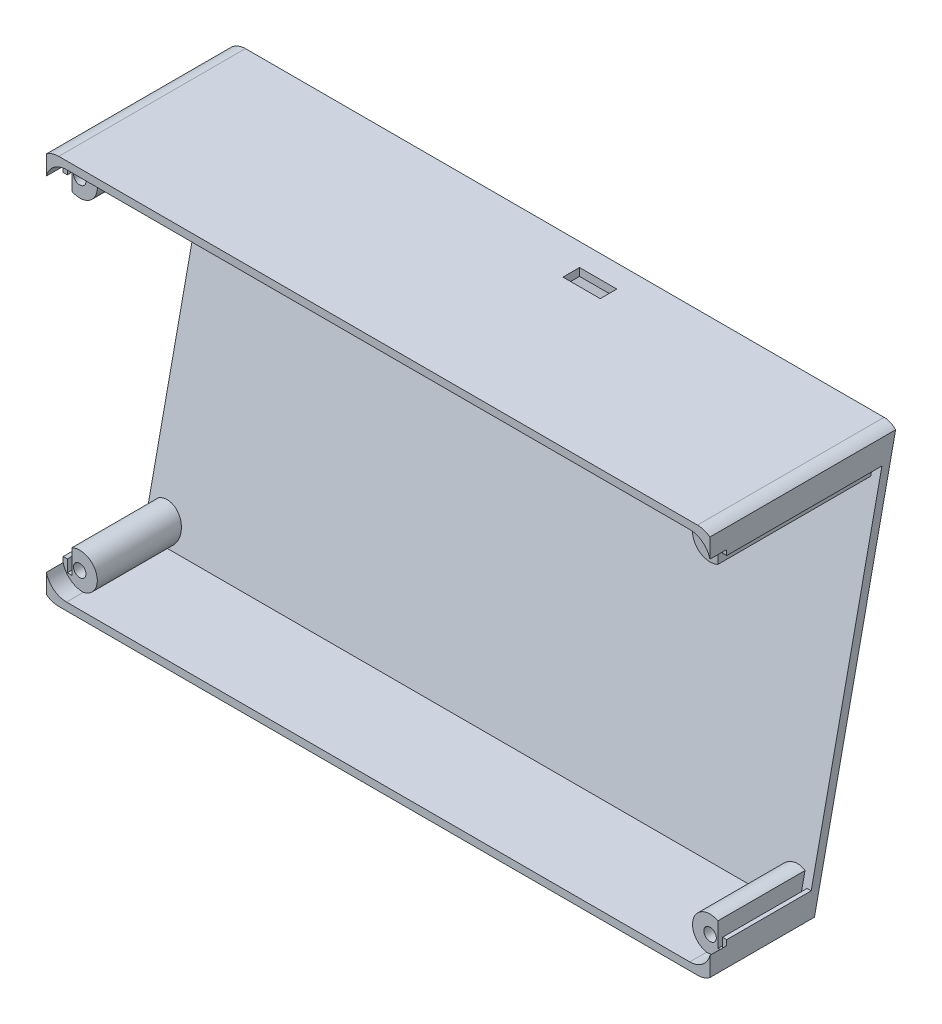
SolidWorks part; units mm, degrees
material "Nylon 101"
ref_plane "Ebene vorne" through (0, 0, 0) normal (0, 0, 1) x (1, 0, 0)
ref_plane "Ebene oben" through (0, 0, 0) normal (0, 1, 0) x (1, 0, 0)
ref_plane "Ebene rechts" through (0, 0, 0) normal (1, 0, 0) x (0, 0, -1)
sketch "Skizze1" plane through (0, 0, 0) normal (0, 0, 1) x (1, 0, 0)
  line L1 (-82, -47) -> (82, -47)
  line L2 (-82, -47) -> (-82, 47)
  line L3 (-82, 47) -> (82, 47)
  line L4 (82, -47) -> (82, 47)
  line L5 (-82, -47) -> (82, 47) construction
  line L6 (-82, 47) -> (82, -47) construction
  point P0 (0, 0)
  dimension "D1" = 164
  dimension "D2" = 94
extrude "Aufsatz-Linear austragen1" add sketch "Skizze1" along normal blind 25
sketch "Skizze2" plane through (82, 0, 0) normal (1, 0, 0) x (0, 0, -1)
  line L0 (0, -47) -> (0, 47)
  line L1 (0, 47) -> (20, 47)
  line L2 (20, 47) -> (0, -47)
  dimension "D1" = 20
extrude "Aufsatz-Linear austragen2" add sketch "Skizze2" against normal up to vertex (164 mm away) up to point (-82, 47, 0)
sketch "Skizze3" plane through (0, 0, 25) normal (0, 0, 1) x (1, 0, 0)
  line L1 (-75.15, -45.15) -> (75.15, -45.15)
  line L2 (-80.15, -40.15) -> (-80.15, 40.15)
  line L3 (-75.15, 45.15) -> (75.15, 45.15)
  line L4 (80.15, -40.15) -> (80.15, 40.15)
  line L5 (-80.15, -45.15) -> (80.15, 45.15) construction
  line L6 (-80.15, 45.15) -> (80.15, -45.15) construction
  arc A0 (80.15, 40.15) -> (75.15, 45.15) centre (75.15, 40.15) ccw
  arc A1 (80.15, -40.15) -> (75.15, -45.15) centre (75.15, -40.15) cw
  arc A2 (-80.15, -40.15) -> (-75.15, -45.15) centre (-75.15, -40.15) ccw
  arc A3 (-80.15, 40.15) -> (-75.15, 45.15) centre (-75.15, 40.15) cw
  point P1 (0, 0)
  dimension "D3" = 5
  dimension "D1" = 160.3
  dimension "D2" = 90.3
extrude "Schnitt-Linear austragen1" cut sketch "Skizze3" against normal offset from surface (24.4127 mm away) 2
sketch "Skizze4" plane through (0, 0, 25) normal (0, 0, 1) x (1, 0, 0)
  line L0 (75.15, 45.15) -> (-75.15, 45.15) construction
  line L1 (-80.15, 40.15) -> (-80.15, -40.15) construction
  line L2 (-75.15, -45.15) -> (75.15, -45.15) construction
  line L3 (80.15, -40.15) -> (80.15, 40.15) construction
  circle A0 centre (-76, 41) radius 1.5
  circle A1 centre (-76, 41) radius 4.2362
  circle A2 centre (-76, -41) radius 1.5
  circle A3 centre (-76, -41) radius 4.2362
  circle A4 centre (76, -41) radius 1.5
  circle A5 centre (76, -41) radius 4.2362
  circle A6 centre (76, 41) radius 1.5
  circle A7 centre (76, 41) radius 4.2362
  dimension "D3" = 3
  dimension "D4" = 3
  dimension "D7" = 3
  dimension "D10" = 3
  dimension "D1" = 4.15
  dimension "D2" = 4.15
  dimension "D5" = 4.15
  dimension "D6" = 4.15
  dimension "D8" = 4.15
  dimension "D9" = 4.15
  dimension "D11" = 4.15
  dimension "D12" = 4.15
extrude "Aufsatz-Linear austragen3" add sketch "Skizze4" against normal up to surface (41.6786 mm away)
sketch "Skizze6" plane through (0, 0, 25) normal (0, 0, 1) x (1, 0, 0)
  line L0 (-75.15, -45.15) -> (75.15, -45.15)
  line L1 (-80.15, -40.15) -> (-80.15, 40.15)
  line L2 (-75.15, 45.15) -> (75.15, 45.15)
  line L3 (80.15, -40.15) -> (80.15, 40.15)
  line L4 (-80.15, -45.15) -> (80.15, 45.15) construction
  line L5 (-80.15, 45.15) -> (80.15, -45.15) construction
  arc A0 (80.15, 40.15) -> (75.15, 45.15) centre (75.15, 40.15) ccw
  arc A1 (80.15, -40.15) -> (75.15, -45.15) centre (75.15, -40.15) cw
  arc A2 (-80.15, -40.15) -> (-75.15, -45.15) centre (-75.15, -40.15) ccw
  arc A3 (-80.15, 40.15) -> (-75.15, 45.15) centre (-75.15, 40.15) cw
  point P0 (0, 0)
  dimension "D3" = 5
  dimension "D1" = 160.3
  dimension "D2" = 90.3
  dimension "D4" = 0
  dimension "D5" = 0
extrude "Schnitt-Linear austragen2" cut sketch "Skizze6" against normal blind 4.05
fillet "Verrundung1" radius 5 4 edges at (82, 47, 2.5) (-82, 47, 2.5) (-82, -47, 12.5) (82, -47, 12.5)
sketch "Skizze7" plane through (0, 47, 0) normal (0, 1, 0) x (1, 0, 0)
  line L0 (75.15, 17.5616) -> (-75.15, 17.5616) construction
  line L1 (9, 14.5616) -> (18, 14.5616)
  line L2 (9, 14.5616) -> (9, 10.5616)
  line L3 (9, 10.5616) -> (18, 10.5616)
  line L4 (18, 14.5616) -> (18, 10.5616)
  line L5 (9, 14.5616) -> (18, 10.5616) construction
  line L6 (9, 10.5616) -> (18, 14.5616) construction
  point P0 (13.5, 12.5616)
  dimension "D1" = 13.5
  dimension "D2" = 3
  dimension "D3" = 9
  dimension "D4" = 4
extrude "Schnitt-Linear austragen4" cut sketch "Skizze7" against normal blind 4.05
sketch "Skizze8" plane through (0, -2.0355, -9.5669) normal (0, -0.2081, -0.9781) x (-1, 0, 0)
  line L0 (-82, -40.8591) -> (-82, 45.0212) construction
  line L1 (77, 50.1331) -> (-77, 50.1331) construction
  line L2 (82, -40.8591) -> (82, 45.0212) construction
  line L3 (77, -45.971) -> (-77, -45.971) construction
  circle A0 centre (-72, 40.1331) radius 5.5
  circle A1 centre (72, 40.1331) radius 5.5
  circle A2 centre (72, -35.971) radius 5.5
  circle A3 centre (-72, -35.971) radius 5.5
  dimension "D1" = 11
  dimension "D4" = 11
  dimension "D7" = 11
  dimension "D10" = 11
  dimension "D2" = 10
  dimension "D3" = 10
  dimension "D5" = 10
  dimension "D6" = 10
  dimension "D8" = 10
  dimension "D9" = 10
  dimension "D11" = 10
  dimension "D12" = 10
extrude "Schnitt-Linear austragen5" cut sketch "Skizze8" against normal blind 1
sketch "Skizze9" plane through (0, 0, 25) normal (0, 0, 1) x (1, 0, 0)
  line L2 (80, -71.5939) -> (80, 71.5939)
  line L4 (-80, -71.5939) -> (-80, 71.5939)
  line L7 (-80, 71.5939) -> (-121.6606, 71.5939)
  line L9 (-80, -71.5939) -> (-121.6606, -71.5939)
  line L10 (-121.6606, 71.5939) -> (-121.6606, -71.5939)
  line L11 (80, 71.5939) -> (127.6666, 71.5939)
  line L13 (80, -71.5939) -> (127.6666, -71.5939)
  line L14 (127.6666, 71.5939) -> (127.6666, -71.5939)
  point P0 (0, 0)
  dimension "D1" = 160
extrude "Schnitt-Linear austragen6" cut sketch "Skizze9" against normal through all
sketch "Skizze11" plane through (0, 0, 20.95) normal (0, 0, 1) x (1, 0, 0)
  line L0 (-80, 39.6054) -> (-80, -39.6054) construction
  line L1 (-77.9, 43) -> (-79, 43)
  line L2 (-77.9, 43) -> (-77.9, -43)
  line L3 (-77.9, -43) -> (-79, -43)
  line L4 (-79, 43) -> (-79, 40.1)
  line L6 (-79, 40.1) -> (-80, 40.1)
  line L8 (-79, -40.1) -> (-80, -40.1)
  line L9 (-80, 40.1) -> (-80, -40.1)
  line L17 (0, -24.75) -> (0, 24.75) construction
  line L18 (80, 40.1) -> (80, -40.1)
  line L19 (79, -40.1) -> (80, -40.1)
  line L21 (79, 40.1) -> (80, 40.1)
  line L22 (79, 43) -> (79, 40.1)
  line L23 (77.9, -43) -> (79, -43)
  line L24 (77.9, 43) -> (77.9, -43)
  line L25 (77.9, 43) -> (79, 43)
  line L26 (-79, -40.1) -> (-79, -43)
  line L27 (79, -40.1) -> (79, -43)
  dimension "D1" = 1
  dimension "D2" = 1.1
  dimension "D3" = 1
  dimension "D4" = 40.1
  dimension "D5" = 40.1
  dimension "D6" = 86
  dimension "D7" = 43
extrude "Schnitt-Linear austragen7" cut sketch "Skizze11" against normal up to surface (38.0542 mm away)
sketch "Skizze12" plane through (-80, 0, 0) normal (-1, 0, 0) x (0, 0, 1)
  line L0 (-16.4871, 40.1) -> (20.95, 40.1) construction
  line L1 (-16.4871, 40.1) -> (20.95, 40.1)
  line L5 (0.5767, -40.1) -> (-16.4871, 40.1)
  line L6 (0.5767, -40.1) -> (20.95, -40.1)
  line L7 (20.95, -40.1) -> (20.95, 40.1)
  dimension "D1" = 37.4371
  dimension "D2" = 80.2
  dimension "D3" = 80.2
  dimension "D4" = 20.3733
